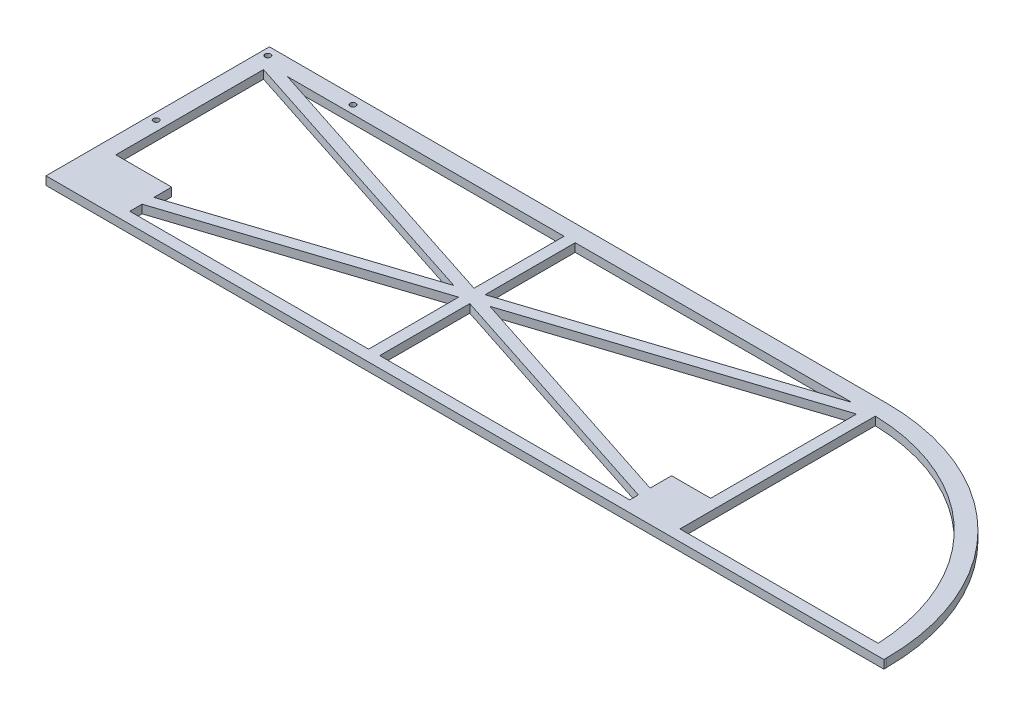
SolidWorks part; units mm, degrees
material "轻木"
ref_plane "前视基准面" through (0, 0, 0) normal (0, 0, 1) x (1, 0, 0)
ref_plane "上视基准面" through (0, 0, 0) normal (0, 1, 0) x (1, 0, 0)
ref_plane "右视基准面" through (0, 0, 0) normal (1, 0, 0) x (0, 0, -1)
other "Configuration Table"
sketch "草图1" plane through (0, 0, 0) normal (0, 1, 0) x (1, 0, 0)
  line L31 (-111.0578, 34) -> (-111.0578, 40) construction
  line L32 (-150, 40) -> (71, 40)
  line L37 (-150, 40) -> (-150, -40)
  line L60 (-150, -40) -> (150, -40)
  line L62 (150, -39) -> (150, -40)
  line L64 (-150, 40) -> (150, -40) construction
  line L72 (-150, -40) -> (150, 40) construction
  line L73 (-117.0578, 37) -> (-147.5578, 37) construction
  line L74 (-147.5578, 37) -> (-147.5578, -3) construction
  line L75 (-144.5578, -10) -> (-144.5578, 34) construction
  arc A5 (71, 40) -> (150, -39) centre (71, -39) cw
  circle A6 centre (-117.0578, 37) radius 1
  circle A7 centre (-147.5578, 37) radius 1
  circle A8 centre (-147.5578, -3) radius 1
  point P0 (0, 0)
  point P13 (-111.0578, 37)
  dimension "D3" = 79
  dimension "D4" = 2
  dimension "D1" = 80
  dimension "D2" = 300
  dimension "D9" = 3
  dimension "D5" = 6
  dimension "D6" = 40
  dimension "D7" = 2
  dimension "D8" = 2
extrude "凸台-拉伸1" add sketch "草图1" along normal blind 3
sketch "草图4" plane through (0, 0, 0) normal (0, 1, 0) x (1, 0, 0)
  line L4 (71, 34) -> (-144, 34)
  line L9 (-144, 34) -> (-144, -36)
  line L10 (71, 34) -> (71, -36) construction
  line L11 (71, 36) -> (-146, 36)
  line L12 (-146, 36) -> (-146, -36)
  line L13 (-146, -36) -> (145.94, -36)
  line L14 (71, 36) -> (-146, 36) construction
  line L15 (-146, 36) -> (-146, -36) construction
  line L16 (-144, -36) -> (143.9383, -36)
  line L17 (-144, 34) -> (71, -36) construction
  line L19 (71, 34) -> (-144, -36) construction
  line L21 (-36.5, -36) -> (-36.5, 34) construction
  line L22 (-34.5, -36) -> (-34.5, 34)
  line L23 (-144, 31.8967) -> (64.5398, -36)
  line L24 (73, 34) -> (73, -36)
  line L25 (64.5398, 34) -> (-144, -33.8967)
  line L26 (-38.5, -36) -> (-38.5, 34)
  line L27 (-137.5398, 34) -> (69, -33.2455)
  line L28 (69, 34) -> (69, -33.2455)
  line L29 (71.6192, 32.0983) -> (71, 31.8967)
  line L30 (-144.6192, 32.0983) -> (73, -38.7545) construction
  line L31 (73, 34) -> (73, -38.7545) construction
  line L32 (70.3808, 35.9017) -> (-144.6192, -34.0983) construction
  line L33 (69, 31.2455) -> (-137.5398, -36)
  line L34 (71.6192, 32.0983) -> (-143.3808, -37.9017) construction
  line L35 (-143.3808, 35.9017) -> (69, -33.2455) construction
  line L37 (69, -36) -> (55, -36)
  line L38 (69, -36) -> (69, -21)
  line L39 (69, -21) -> (55, -21)
  line L40 (55, -36) -> (55, -21)
  line L41 (-144, -36) -> (-124, -36)
  line L42 (-144, -36) -> (-144, -21)
  line L43 (-144, -21) -> (-124, -21)
  line L44 (-124, -36) -> (-124, -21)
  arc A3 (145.94, -36) -> (71, 36) centre (71, -39) ccw
  arc A4 (145.94, -36) -> (71, 36) centre (71, -39) ccw construction
  arc A5 (143.9383, -36) -> (71, 34) centre (71, -39) ccw
  arc A6 (143.9416, -36.08) -> (71, 34) centre (71, -39) ccw construction
  dimension "D2" = 2
  dimension "D3" = 2
  dimension "D5" = 15
  dimension "D7" = 20
  dimension "D8" = 15
  dimension "D6" = 14
  dimension "D1" = 4
  dimension "D4" = 2
extrude "切除-拉伸2" cut sketch "草图4" along normal blind 18
